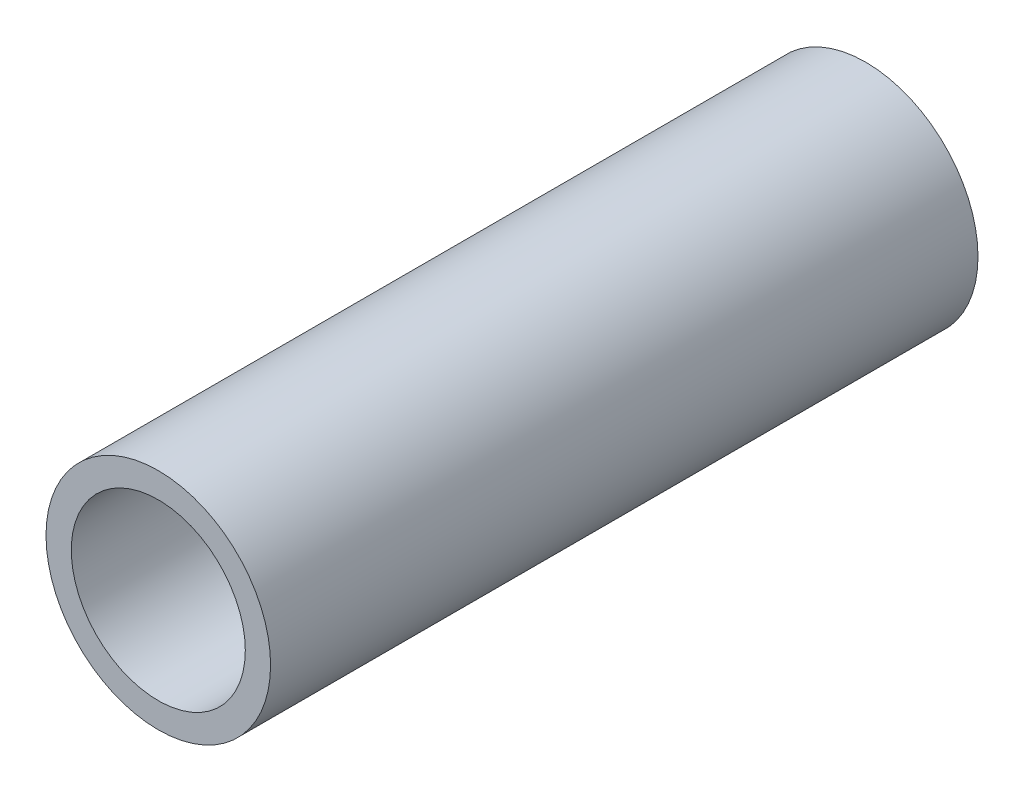
SolidWorks part; units mm, degrees
ref_plane "Спереди" through (0, 0, 0) normal (0, 0, 1) x (1, 0, 0)
ref_plane "Сверху" through (0, 0, 0) normal (0, 1, 0) x (1, 0, 0)
ref_plane "Справа" through (0, 0, 0) normal (1, 0, 0) x (0, 0, -1)
sketch "Эскиз1" plane through (0, 0, 0) normal (0, 0, 1) x (1, 0, 0)
  circle A0 centre (0, 0) radius 1
  circle A1 centre (0, 0) radius 0.775
extrude "Бобышка-Вытянуть1" add sketch "Эскиз1" along normal blind 6.3
